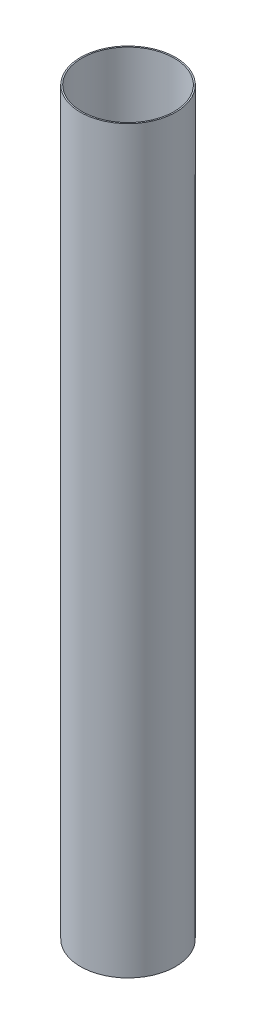
SolidWorks part; units mm, degrees
ref_plane "Front Plane" through (0, 0, 0) normal (0, 0, 1) x (1, 0, 0)
ref_plane "Top Plane" through (0, 0, 0) normal (0, 1, 0) x (1, 0, 0)
ref_plane "Right Plane" through (0, 0, 0) normal (1, 0, 0) x (0, 0, -1)
sketch "Sketch1" plane through (0, 0, 0) normal (0, 1, 0) x (1, 0, 0)
  circle A0 centre (0, 0) radius 76.2
  circle A1 centre (0, 0) radius 78.4225
  dimension "D1" = 156.845
  dimension "D2" = 152.4
extrude "Boss-Extrude1" add sketch "Sketch1" along normal blind 1219.2
